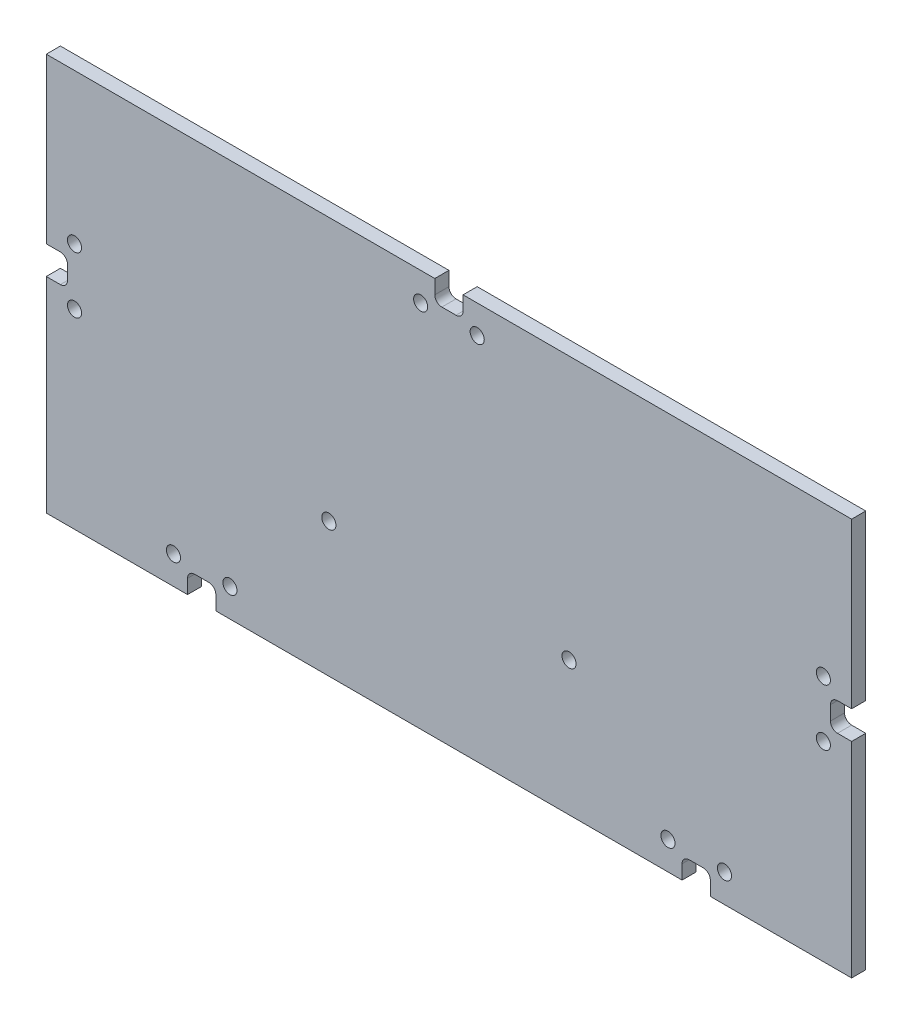
SolidWorks part; units mm, degrees
material "自訂玻璃纖維"
ref_plane "前基準面" through (0, 0, 0) normal (0, 0, 1) x (1, 0, 0)
ref_plane "上基準面" through (0, 0, 0) normal (0, 1, 0) x (1, 0, 0)
ref_plane "右基準面" through (0, 0, 0) normal (1, 0, 0) x (0, 0, -1)
sketch "草圖1" plane through (0, 0, 0) normal (0, 0, 1) x (1, 0, 0)
  line L0 (23.8615, 13.2435) -> (25.8615, 13.2435)
  line L1 (-31.1385, 16.2435) -> (22.8615, 16.2435)
  line L2 (-32.1385, 15.2435) -> (-32.1385, -7.0065)
  line L3 (-31.1385, -40.0065) -> (-12.1385, -40.0065)
  line L4 (81.8615, 15.2435) -> (81.8615, -7.0065)
  line L5 (-29.1385, -8.0065) -> (-29.1385, -10.0065)
  line L6 (22.8615, 16.2435) -> (22.8615, 14.2435)
  line L7 (26.8615, 16.2435) -> (80.8615, 16.2435)
  line L8 (26.8615, 16.2435) -> (26.8615, 14.2435)
  line L9 (-32.1385, -7.0065) -> (-30.1385, -7.0065)
  line L10 (81.8615, -11.0065) -> (81.8615, -39.0065)
  line L11 (-32.1385, -11.0065) -> (-30.1385, -11.0065)
  line L12 (-32.1385, -11.0065) -> (-32.1385, -39.0065)
  line L13 (81.8615, -11.0065) -> (79.8615, -11.0065)
  line L14 (81.8615, -7.0065) -> (79.8615, -7.0065)
  line L15 (78.8615, -8.0065) -> (78.8615, -10.0065)
  line L16 (-11.1385, -37.0065) -> (-9.1385, -37.0065)
  line L17 (58.8615, -37.0065) -> (60.8615, -37.0065)
  line L18 (-12.1385, -40.0065) -> (-12.1385, -38.0065)
  line L19 (-8.1385, -40.0065) -> (57.8615, -40.0065)
  line L20 (-8.1385, -40.0065) -> (-8.1385, -38.0065)
  line L21 (61.8615, -40.0065) -> (61.8615, -38.0065)
  line L22 (57.8615, -40.0065) -> (57.8615, -38.0065)
  line L23 (61.8615, -40.0065) -> (80.8615, -40.0065)
  line L24 (-31.1385, 16.2435) -> (-32.1385, 16.2435)
  line L25 (-32.1385, 16.2435) -> (-32.1385, 15.2435)
  line L26 (-32.1385, -39.0065) -> (-32.1385, -40.0065)
  line L27 (-32.1385, -40.0065) -> (-31.1385, -40.0065)
  line L28 (81.8615, -39.0065) -> (81.8615, -40.0065)
  line L29 (81.8615, -40.0065) -> (80.8615, -40.0065)
  line L30 (81.8615, 15.2435) -> (81.8615, 16.2435)
  line L31 (81.8615, 16.2435) -> (80.8615, 16.2435)
  circle A0 centre (55.8615, -36.0065) radius 1
  arc A1 (-30.1385, -7.0065) -> (-29.1385, -8.0065) centre (-30.1385, -8.0065) cw
  circle A2 centre (77.8615, -5.0065) radius 1
  circle A3 centre (-6.1385, -36.0065) radius 1
  circle A8 centre (28.8615, 12.2435) radius 1
  circle A9 centre (20.8615, 12.2435) radius 1
  arc A10 (22.8615, 14.2435) -> (23.8615, 13.2435) centre (23.8615, 14.2435) ccw
  arc A11 (25.8615, 13.2435) -> (26.8615, 14.2435) centre (25.8615, 14.2435) ccw
  circle A12 centre (-28.1385, -5.0065) radius 1
  circle A13 centre (-28.1385, -13.0065) radius 1
  circle A14 centre (77.8615, -13.0065) radius 1
  circle A15 centre (-14.1385, -36.0065) radius 1
  circle A16 centre (63.8615, -36.0065) radius 1
  arc A17 (-29.1385, -10.0065) -> (-30.1385, -11.0065) centre (-30.1385, -10.0065) cw
  arc A18 (78.8615, -10.0065) -> (79.8615, -11.0065) centre (79.8615, -10.0065) ccw
  arc A19 (79.8615, -7.0065) -> (78.8615, -8.0065) centre (79.8615, -8.0065) ccw
  arc A20 (-12.1385, -38.0065) -> (-11.1385, -37.0065) centre (-11.1385, -38.0065) cw
  arc A21 (-9.1385, -37.0065) -> (-8.1385, -38.0065) centre (-9.1385, -38.0065) cw
  arc A22 (57.8615, -38.0065) -> (58.8615, -37.0065) centre (58.8615, -38.0065) cw
  arc A23 (60.8615, -37.0065) -> (61.8615, -38.0065) centre (60.8615, -38.0065) cw
  point P14 (-32.1385, -40.0065)
  point P19 (81.8615, 16.2435)
  point P22 (-32.1385, 16.2435)
  dimension "D3" = 4
  dimension "D4" = 2
  dimension "D5" = 27
  dimension "D6" = 2
  dimension "D7" = 4
  dimension "D8" = 8
  dimension "D9" = 18
  dimension "D10" = 2
  dimension "D11" = 2
  dimension "D12" = 18
  dimension "D13" = 2
  dimension "D17" = 8
  dimension "D18" = 2
  dimension "D19" = 8
  dimension "D20" = 4
  dimension "D1" = 114
  dimension "D2" = 56.25
  dimension "D21" = 2
  dimension "D22" = 4
  dimension "D23" = 2
extrude "填料-伸長1" add sketch "草圖1" along normal blind 2
sketch "草圖2" plane through (0, 0, 2) normal (0, 0, 1) x (1, 0, 0)
  line L1 (-32.1385, -40.0065) -> (-12.1385, -40.0065) construction
  circle A0 centre (7.8615, -21.0065) radius 1
  circle A1 centre (41.8615, -21.0065) radius 1
  dimension "D1" = 19
  dimension "D2" = 19
  dimension "D3" = 2
extrude "除料-伸長1" cut sketch "草圖2" against normal blind 10
